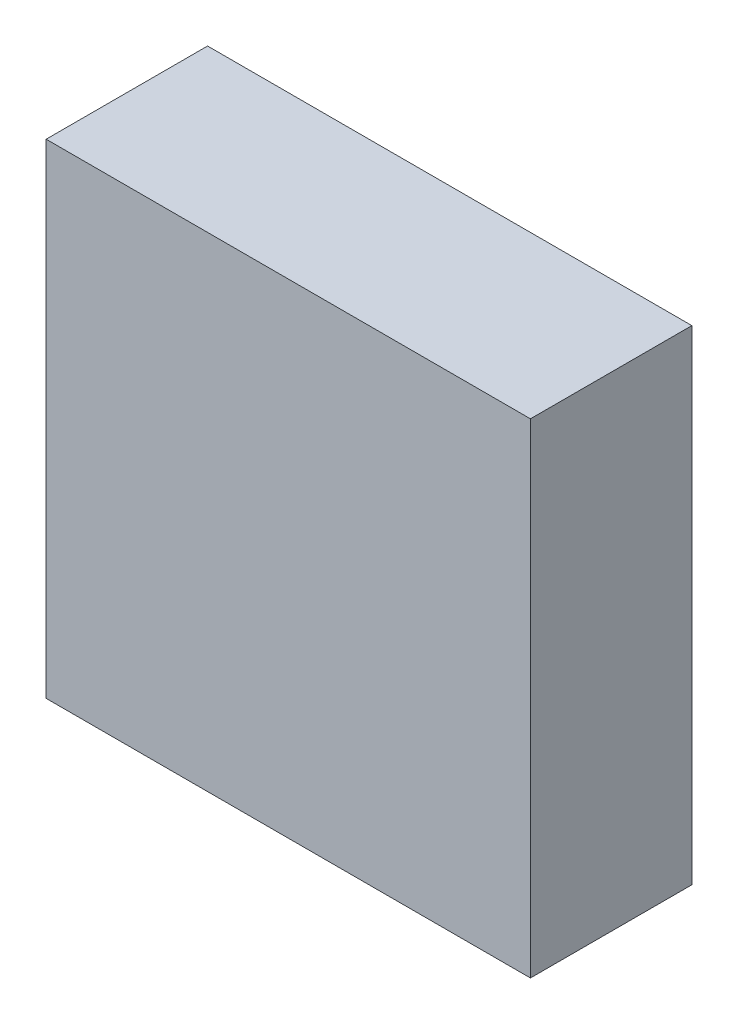
SolidWorks part; units mm, degrees
ref_plane "Front Plane" through (0, 0, 0) normal (0, 0, 1) x (1, 0, 0)
ref_plane "Top Plane" through (0, 0, 0) normal (0, 1, 0) x (1, 0, 0)
ref_plane "Right Plane" through (0, 0, 0) normal (1, 0, 0) x (0, 0, -1)
ref_plane "Plane1" through (0, 0, 0) normal (0, 0, -1) x (-1, 0, 0)
sketch "Sketch1" plane through (0, 0, 0) normal (0, 0, -1) x (-1, 0, 0)
  line L0 (-2.5599, -0.566) -> (-2.5599, -3.566)
  line L1 (-2.5599, -3.566) -> (0.4401, -3.566)
  line L2 (0.4401, -3.566) -> (0.4401, -0.566)
  line L3 (0.4401, -0.566) -> (-2.5599, -0.566)
extrude "Boss-Extrude1" add sketch "Sketch1" against normal blind 1
